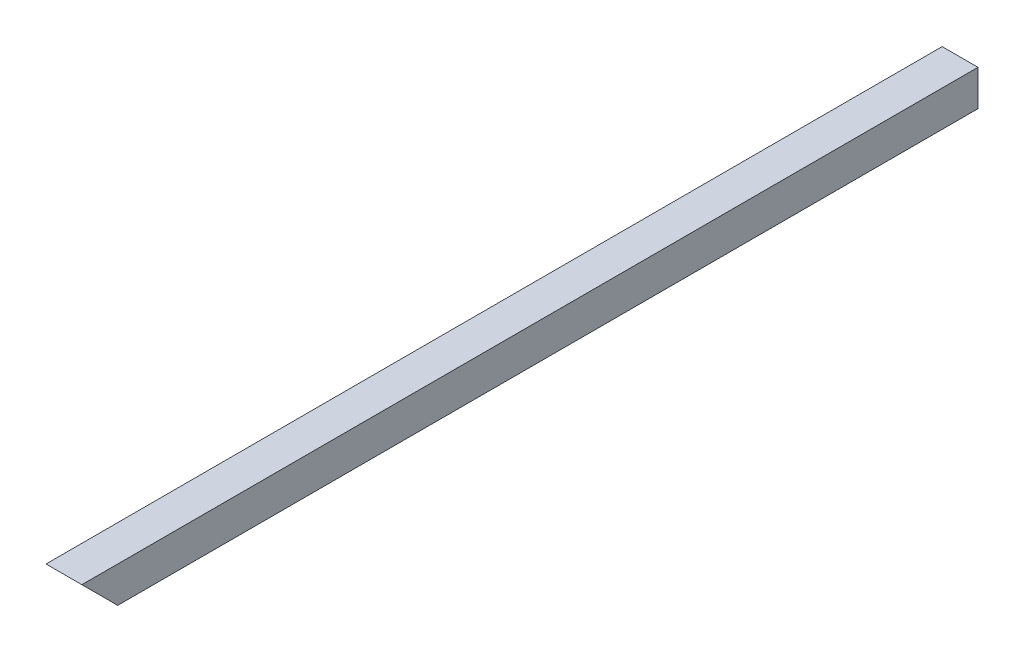
SolidWorks part; units mm, degrees
ref_plane "Front Plane" through (0, 0, 0) normal (0, 0, 1) x (1, 0, 0)
ref_plane "Top Plane" through (0, 0, 0) normal (0, 1, 0) x (1, 0, 0)
ref_plane "Right Plane" through (0, 0, 0) normal (1, 0, 0) x (0, 0, -1)
sketch "Sketch1" plane through (0, 0, 0) normal (0, 0, 1) x (1, 0, 0)
  line L1 (-25, -25) -> (25, -25)
  line L2 (-25, -25) -> (-25, 25)
  line L3 (-25, 25) -> (25, 25)
  line L4 (25, -25) -> (25, 25)
  line L5 (-25, -25) -> (25, 25) construction
  line L6 (-25, 25) -> (25, -25) construction
  line L7 (-23, -23) -> (23, -23)
  line L8 (-23, -23) -> (-23, 23)
  line L9 (-23, 23) -> (23, 23)
  line L10 (23, -23) -> (23, 23)
  line L11 (-23, -23) -> (23, 23) construction
  line L12 (-23, 23) -> (23, -23) construction
  point P0 (0, 0)
  point P6 (0, 0)
  dimension "D1" = 50
  dimension "D2" = 46
extrude "Boss-Extrude1" add sketch "Sketch1" along normal blind 1250
sketch "Sketch2" plane through (25, 0, 0) normal (1, 0, 0) x (0, 0, -1)
  line L0 (-1250, 25) -> (-1250, -25)
  line L1 (-1250, 25) -> (0, 25) construction
  line L2 (-1250, -25) -> (-1250, 25) construction
  line L3 (-1250, -25) -> (-1200, -25)
  line L4 (-1250, -25) -> (0, -25) construction
  line L5 (-1200, -25) -> (-1250, 25)
extrude "Cut-Extrude1" cut sketch "Sketch2" against normal through all
